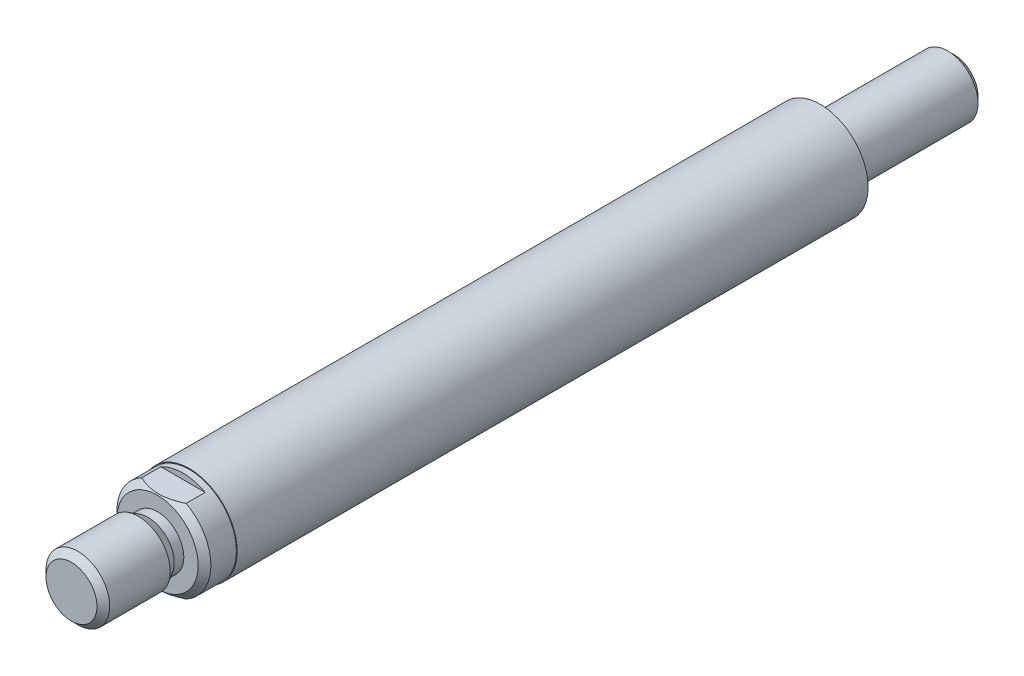
SolidWorks part; units mm, degrees
ref_plane "Plan1" through (0, 0, 0) normal (0, 0, 1) x (1, 0, 0)
ref_plane "Plan2" through (0, 0, 0) normal (0, 1, 0) x (1, 0, 0)
ref_plane "Plan3" through (0, 0, 0) normal (1, 0, 0) x (0, 0, -1)
sketch "Esquisse1" plane through (0, 0, 0) normal (0, 0, 1) x (1, 0, 0)
  circle A0 centre (0, 0) radius 15
  dimension "D1" = 30
extrude "tige" add sketch "Esquisse1" along normal blind 277
sketch "Esquisse2" plane through (0, 0, 277) normal (0, 0, 1) x (1, 0, 0)
  circle A0 centre (0, 0) radius 14.75
  dimension "D1" = 29.5
extrude "centrage de chape" cut sketch "Esquisse2" against normal blind 37 flip side to cut
sketch "Esquisse3" plane through (0, 0, 277) normal (0, 0, 1) x (1, 0, 0)
  circle A0 centre (0, 0) radius 10
  dimension "D1" = 20
extrude "diamètre de filetage" cut sketch "Esquisse3" against normal blind 27 flip side to cut
sketch "Esquisse4" plane through (0, 0, 250) normal (0, 0, 1) x (1, 0, 0)
  circle A0 centre (0, 0) radius 8.25
  dimension "D1" = 16.5
extrude "gorge de dégagement " cut sketch "Esquisse4" along normal blind 3 flip side to cut
sketch "Esquisse5" plane through (0, 0, 253) normal (0, 0, -1) x (-1, 0, 0)
  circle A0 centre (0, 0) radius 8.25 construction
  circle A1 centre (0, 0) radius 8.25
extrude "chanfrein de dégagement" cut sketch "Esquisse5" against normal blind 3 draft 30 flip side to cut
chamfer "Chanfrein4" distance 2 angle 45
ref_plane "Plan4" through (0, 13, 0) normal (0, 1, 0) x (-1, 0, 0)
sketch "Esquisse6" plane through (0, 13, 0) normal (0, 1, 0) x (-1, 0, 0)
  line L1 (-14.75, 242) -> (14.75, 242)
  line L2 (14.75, 250) -> (-14.75, 250) construction
  line L3 (14.75, 250) -> (-14.75, 250)
  line L4 (14.75, 250) -> (14.75, 242)
  line L5 (-14.75, 250) -> (-14.75, 242)
  line L6 (15, 240) -> (-15, 240) construction
  dimension "D1" = 2
extrude "méplat 1" cut sketch "Esquisse6" along normal up to next
mirror "méplat 2" about plane through (0, 0, 0) normal (0, 1, 0)
sketch "Esquisse7" plane through (0, 0, 0) normal (0, 0, -1) x (-1, 0, 0)
  circle A0 centre (0, 0) radius 9.5
  dimension "D1" = 19
extrude "centrage de piston" cut sketch "Esquisse7" against normal blind 42 flip side to cut
chamfer "Chanfrein de filetage" distance 2 angle 45
